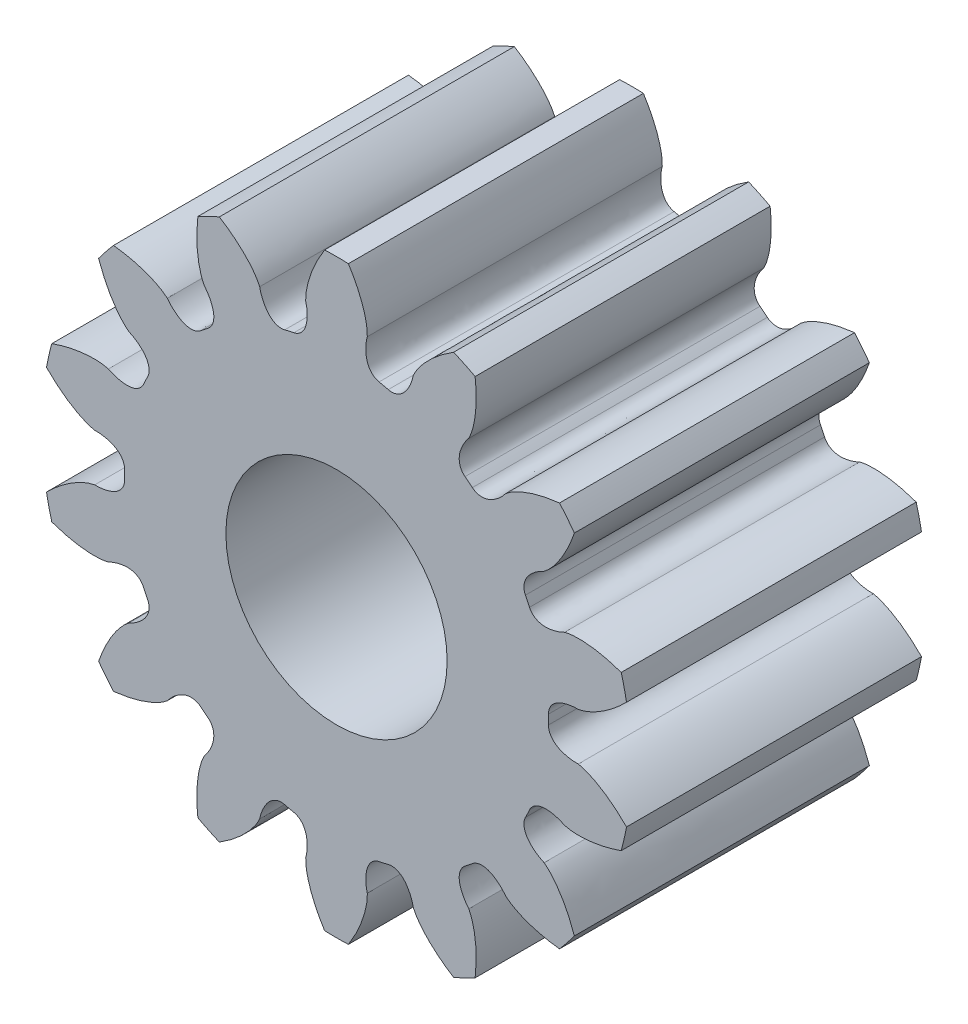
SolidWorks part; units mm, degrees
ref_plane "Спереди" through (0, 0, 0) normal (0, 0, 1) x (1, 0, 0)
ref_plane "Сверху" through (0, 0, 0) normal (0, 1, 0) x (1, 0, 0)
ref_plane "Справа" through (0, 0, 0) normal (1, 0, 0) x (0, 0, -1)
sketch "Sketch1" plane through (0, 0, 0) normal (0, 0, 1) x (1, 0, 0)
  line L0 (0, 0) -> (-5.5, 0) construction
  line L1 (0, 0) -> (5.5, 0) construction
  line L2 (0, 0) -> (0, -5.5) construction
  line L3 (0, 0) -> (0, 5.5) construction
  arc A60 (0.1615, 3.9967) -> (-0.1615, 3.9967) centre (0, 0) ccw
  arc A61 (-0.5774, 2.8164) -> (-0.7018, 2.788) centre (0, 0) ccw
  arc A62 (-1.5887, 3.671) -> (-1.8796, 3.5309) centre (0, 0) ccw
  arc A63 (-1.7422, 2.287) -> (-1.842, 2.2074) centre (0, 0) ccw
  arc A64 (-3.0241, 2.6182) -> (-3.2254, 2.3657) centre (0, 0) ccw
  arc A65 (-2.562, 1.3046) -> (-2.6173, 1.1896) centre (0, 0) ccw
  arc A66 (-3.8606, 1.0468) -> (-3.9325, 0.732) centre (0, 0) ccw
  arc A67 (-2.8743, 0.0638) -> (-2.8743, -0.0638) centre (0, 0) ccw
  arc A68 (-3.9325, -0.732) -> (-3.8606, -1.0468) centre (0, 0) ccw
  arc A69 (-2.6173, -1.1896) -> (-2.562, -1.3046) centre (0, 0) ccw
  arc A70 (-3.2254, -2.3657) -> (-3.0241, -2.6182) centre (0, 0) ccw
  arc A71 (-1.842, -2.2074) -> (-1.7422, -2.287) centre (0, 0) ccw
  arc A72 (-1.8796, -3.5309) -> (-1.5887, -3.671) centre (0, 0) ccw
  arc A73 (-0.7018, -2.788) -> (-0.5774, -2.8164) centre (0, 0) ccw
  arc A74 (-0.1615, -3.9967) -> (0.1615, -3.9967) centre (0, 0) ccw
  arc A75 (0.5774, -2.8164) -> (0.7018, -2.788) centre (0, 0) ccw
  arc A76 (1.5887, -3.671) -> (1.8796, -3.5309) centre (0, 0) ccw
  arc A77 (1.7422, -2.287) -> (1.842, -2.2074) centre (0, 0) ccw
  arc A78 (3.0241, -2.6182) -> (3.2254, -2.3657) centre (0, 0) ccw
  arc A79 (2.562, -1.3046) -> (2.6173, -1.1896) centre (0, 0) ccw
  arc A80 (3.8606, -1.0468) -> (3.9325, -0.732) centre (0, 0) ccw
  arc A81 (2.8743, -0.0638) -> (2.8743, 0.0638) centre (0, 0) ccw
  arc A82 (3.9325, 0.732) -> (3.8606, 1.0468) centre (0, 0) ccw
  arc A83 (2.6173, 1.1896) -> (2.562, 1.3046) centre (0, 0) ccw
  arc A84 (3.2254, 2.3657) -> (3.0241, 2.6182) centre (0, 0) ccw
  arc A85 (1.842, 2.2074) -> (1.7422, 2.287) centre (0, 0) ccw
  arc A86 (1.8796, 3.5309) -> (1.5887, 3.671) centre (0, 0) ccw
  arc A87 (0.7018, 2.788) -> (0.5774, 2.8164) centre (0, 0) ccw
  circle A88 centre (0, 0) radius 3.5 construction
  spline S0 degree 3 poles (0.4173, 3.2671) (0.4021, 3.2094) (0.3957, 3.1517) (0.3981, 3.0941) (0.3993, 3.0639) (0.4019, 3.033) (0.409, 3.0037) (0.4137, 2.9844) (0.4196, 2.9649) (0.4276, 2.9468) (0.4338, 2.933) (0.4408, 2.9193) (0.4492, 2.9068) (0.4561, 2.8963) (0.4638, 2.8861) (0.4724, 2.8769) (0.4799, 2.8687) (0.4882, 2.861) (0.497, 2.8541) (0.5051, 2.8477) (0.5137, 2.8419) (0.5227, 2.8368) (0.5313, 2.832) (0.5403, 2.8278) (0.5496, 2.8244) (0.5586, 2.8211) (0.5678, 2.8184) (0.5774, 2.8164) knots 0 0 0 0 1 1 1 2 2 2 3 3 3 4 4 4 5 5 5 6 6 6 7 7 7 8 8 8 9 9 9 9
  spline S1 degree 3 poles (-0.4173, 3.2671) (-0.4021, 3.2094) (-0.3957, 3.1517) (-0.3981, 3.0941) (-0.3993, 3.0639) (-0.4019, 3.033) (-0.409, 3.0037) (-0.4137, 2.9844) (-0.4196, 2.9649) (-0.4276, 2.9468) (-0.4338, 2.933) (-0.4408, 2.9193) (-0.4492, 2.9068) (-0.4561, 2.8963) (-0.4638, 2.8861) (-0.4724, 2.8769) (-0.4799, 2.8687) (-0.4882, 2.861) (-0.497, 2.8541) (-0.5051, 2.8477) (-0.5137, 2.8419) (-0.5227, 2.8368) (-0.5313, 2.832) (-0.5403, 2.8278) (-0.5496, 2.8244) (-0.5586, 2.8211) (-0.5678, 2.8184) (-0.5774, 2.8164) knots 0 0 0 0 1 1 1 2 2 2 3 3 3 4 4 4 5 5 5 6 6 6 7 7 7 8 8 8 9 9 9 9
  spline S2 degree 3 poles (0.4173, 3.2671) (0.4181, 3.2937) (0.4172, 3.3202) (0.4149, 3.3465) (0.4125, 3.3735) (0.408, 3.4004) (0.403, 3.427) (0.3978, 3.4543) (0.3913, 3.4813) (0.3842, 3.5081) (0.3769, 3.5355) (0.3685, 3.5627) (0.3596, 3.5896) (0.3504, 3.6171) (0.3403, 3.6444) (0.3296, 3.6713) (0.3186, 3.6988) (0.3069, 3.7261) (0.2946, 3.753) (0.282, 3.7805) (0.2687, 3.8077) (0.2548, 3.8346) (0.2406, 3.862) (0.2257, 3.8891) (0.2104, 3.9159) (0.1947, 3.9432) (0.1784, 3.9701) (0.1615, 3.9967) knots 0 0 0 0 1 1 1 2 2 2 3 3 3 4 4 4 5 5 5 6 6 6 7 7 7 8 8 8 9 9 9 9
  spline S3 degree 3 poles (-0.4173, 3.2671) (-0.4181, 3.2937) (-0.4172, 3.3202) (-0.4149, 3.3465) (-0.4125, 3.3735) (-0.408, 3.4004) (-0.403, 3.427) (-0.3978, 3.4543) (-0.3913, 3.4813) (-0.3842, 3.5081) (-0.3769, 3.5355) (-0.3685, 3.5627) (-0.3596, 3.5896) (-0.3504, 3.6171) (-0.3403, 3.6444) (-0.3296, 3.6713) (-0.3186, 3.6988) (-0.3069, 3.7261) (-0.2946, 3.753) (-0.282, 3.7805) (-0.2687, 3.8077) (-0.2548, 3.8346) (-0.2406, 3.862) (-0.2257, 3.8891) (-0.2104, 3.9159) (-0.1947, 3.9432) (-0.1784, 3.9701) (-0.1615, 3.9967) knots 0 0 0 0 1 1 1 2 2 2 3 3 3 4 4 4 5 5 5 6 6 6 7 7 7 8 8 8 9 9 9 9
  spline S4 degree 3 poles (-1.0415, 3.1246) (-1.0302, 3.066) (-1.011, 3.0113) (-0.9838, 2.9604) (-0.9696, 2.9338) (-0.9539, 2.907) (-0.9347, 2.8837) (-0.9221, 2.8683) (-0.9084, 2.8534) (-0.8933, 2.8405) (-0.8818, 2.8307) (-0.8695, 2.8215) (-0.8565, 2.8138) (-0.8457, 2.8073) (-0.8343, 2.8016) (-0.8226, 2.7969) (-0.8123, 2.7929) (-0.8015, 2.7895) (-0.7906, 2.7871) (-0.7805, 2.7849) (-0.7702, 2.7833) (-0.7599, 2.7827) (-0.7501, 2.7821) (-0.7401, 2.7822) (-0.7303, 2.7831) (-0.7208, 2.784) (-0.7112, 2.7857) (-0.7018, 2.788) knots 0 0 0 0 1 1 1 2 2 2 3 3 3 4 4 4 5 5 5 6 6 6 7 7 7 8 8 8 9 9 9 9
  spline S5 degree 3 poles (-1.7936, 2.7625) (-1.7548, 2.7171) (-1.724, 2.6679) (-1.7011, 2.6149) (-1.6892, 2.5872) (-1.6781, 2.5583) (-1.6718, 2.5287) (-1.6676, 2.5093) (-1.6645, 2.4893) (-1.6638, 2.4694) (-1.6634, 2.4543) (-1.6638, 2.439) (-1.6659, 2.424) (-1.6676, 2.4116) (-1.6701, 2.399) (-1.6738, 2.387) (-1.6771, 2.3764) (-1.6812, 2.3658) (-1.6861, 2.3558) (-1.6906, 2.3466) (-1.6959, 2.3375) (-1.7018, 2.3291) (-1.7075, 2.3211) (-1.7138, 2.3133) (-1.7206, 2.3063) (-1.7273, 2.2993) (-1.7345, 2.2929) (-1.7422, 2.287) knots 0 0 0 0 1 1 1 2 2 2 3 3 3 4 4 4 5 5 5 6 6 6 7 7 7 8 8 8 9 9 9 9
  spline S6 degree 3 poles (-1.0415, 3.1246) (-1.0524, 3.1489) (-1.0647, 3.1724) (-1.0782, 3.1951) (-1.092, 3.2184) (-1.1078, 3.2407) (-1.1239, 3.2625) (-1.1403, 3.2848) (-1.1579, 3.3064) (-1.176, 3.3274) (-1.1944, 3.3489) (-1.2138, 3.3698) (-1.2335, 3.3901) (-1.2537, 3.4109) (-1.2747, 3.4311) (-1.296, 3.4507) (-1.3178, 3.4708) (-1.3402, 3.4902) (-1.363, 3.5092) (-1.3862, 3.5285) (-1.4101, 3.5472) (-1.4342, 3.5654) (-1.4589, 3.5839) (-1.484, 3.6019) (-1.5095, 3.6193) (-1.5355, 3.6371) (-1.5619, 3.6544) (-1.5887, 3.671) knots 0 0 0 0 1 1 1 2 2 2 3 3 3 4 4 4 5 5 5 6 6 6 7 7 7 8 8 8 9 9 9 9
  spline S7 degree 3 poles (-1.7936, 2.7625) (-1.8057, 2.7861) (-1.8165, 2.8103) (-1.8258, 2.8351) (-1.8354, 2.8604) (-1.843, 2.8866) (-1.85, 2.9128) (-1.8572, 2.9396) (-1.8631, 2.9668) (-1.8683, 2.994) (-1.8736, 3.0219) (-1.8779, 3.05) (-1.8814, 3.0781) (-1.8851, 3.1069) (-1.8878, 3.1358) (-1.8899, 3.1647) (-1.892, 3.1943) (-1.8932, 3.2239) (-1.8938, 3.2535) (-1.8944, 3.2838) (-1.8942, 3.3141) (-1.8933, 3.3443) (-1.8924, 3.3752) (-1.8908, 3.406) (-1.8886, 3.4368) (-1.8863, 3.4682) (-1.8833, 3.4996) (-1.8796, 3.5309) knots 0 0 0 0 1 1 1 2 2 2 3 3 3 4 4 4 5 5 5 6 6 6 7 7 7 8 8 8 9 9 9 9
  spline S8 degree 3 poles (-2.2941, 2.3633) (-2.2585, 2.3154) (-2.2174, 2.2744) (-2.1708, 2.2403) (-2.1465, 2.2225) (-2.1207, 2.2053) (-2.0933, 2.1926) (-2.0753, 2.1842) (-2.0565, 2.1767) (-2.0372, 2.1716) (-2.0226, 2.1678) (-2.0076, 2.1648) (-1.9925, 2.1635) (-1.98, 2.1624) (-1.9673, 2.1621) (-1.9547, 2.163) (-1.9436, 2.1639) (-1.9324, 2.1655) (-1.9216, 2.168) (-1.9115, 2.1704) (-1.9016, 2.1735) (-1.892, 2.1774) (-1.8829, 2.1811) (-1.874, 2.1856) (-1.8656, 2.1906) (-1.8573, 2.1956) (-1.8495, 2.2012) (-1.842, 2.2074) knots 0 0 0 0 1 1 1 2 2 2 3 3 3 4 4 4 5 5 5 6 6 6 7 7 7 8 8 8 9 9 9 9
  spline S9 degree 3 poles (-2.8145, 1.7107) (-2.7599, 1.6866) (-2.7108, 1.6557) (-2.6672, 1.6179) (-2.6444, 1.5981) (-2.6219, 1.5768) (-2.6034, 1.553) (-2.5912, 1.5372) (-2.5797, 1.5206) (-2.5705, 1.5029) (-2.5635, 1.4896) (-2.5573, 1.4755) (-2.5526, 1.4612) (-2.5488, 1.4492) (-2.5457, 1.4368) (-2.5438, 1.4244) (-2.5421, 1.4134) (-2.5412, 1.4021) (-2.5413, 1.391) (-2.5413, 1.3807) (-2.5422, 1.3702) (-2.5438, 1.3601) (-2.5454, 1.3504) (-2.5478, 1.3407) (-2.5509, 1.3313) (-2.5539, 1.3222) (-2.5576, 1.3133) (-2.562, 1.3046) knots 0 0 0 0 1 1 1 2 2 2 3 3 3 4 4 4 5 5 5 6 6 6 7 7 7 8 8 8 9 9 9 9
  spline S10 degree 3 poles (-2.2941, 2.3633) (-2.3145, 2.3804) (-2.3357, 2.3963) (-2.3577, 2.4109) (-2.3803, 2.4259) (-2.4041, 2.4391) (-2.4281, 2.4518) (-2.4526, 2.4647) (-2.4778, 2.4765) (-2.5032, 2.4877) (-2.5292, 2.499) (-2.5557, 2.5095) (-2.5823, 2.5192) (-2.6095, 2.5292) (-2.6371, 2.5383) (-2.6649, 2.5467) (-2.6932, 2.5553) (-2.7218, 2.5631) (-2.7506, 2.5703) (-2.7799, 2.5776) (-2.8095, 2.5841) (-2.8391, 2.59) (-2.8694, 2.596) (-2.8999, 2.6013) (-2.9304, 2.606) (-2.9615, 2.6107) (-2.9928, 2.6148) (-3.0241, 2.6182) knots 0 0 0 0 1 1 1 2 2 2 3 3 3 4 4 4 5 5 5 6 6 6 7 7 7 8 8 8 9 9 9 9
  spline S11 degree 3 poles (-2.8145, 1.7107) (-2.8358, 1.7268) (-2.856, 1.7439) (-2.8751, 1.7621) (-2.8947, 1.7808) (-2.9129, 1.8011) (-2.9306, 1.8217) (-2.9487, 1.8427) (-2.9658, 1.8646) (-2.9823, 1.8869) (-2.9992, 1.9097) (-3.0152, 1.9332) (-3.0307, 1.957) (-3.0464, 1.9813) (-3.0614, 2.0062) (-3.0758, 2.0313) (-3.0905, 2.0571) (-3.1045, 2.0832) (-3.1179, 2.1097) (-3.1315, 2.1366) (-3.1445, 2.164) (-3.1568, 2.1916) (-3.1695, 2.2198) (-3.1814, 2.2483) (-3.1927, 2.277) (-3.2043, 2.3063) (-3.2152, 2.3359) (-3.2254, 2.3657) knots 0 0 0 0 1 1 1 2 2 2 3 3 3 4 4 4 5 5 5 6 6 6 7 7 7 8 8 8 9 9 9 9
  spline S12 degree 3 poles (-3.0923, 1.1339) (-3.0394, 1.1062) (-2.9846, 1.0871) (-2.9279, 1.0766) (-2.8982, 1.0711) (-2.8675, 1.0667) (-2.8373, 1.0672) (-2.8175, 1.0674) (-2.7972, 1.0688) (-2.7777, 1.0726) (-2.7629, 1.0755) (-2.748, 1.0794) (-2.7339, 1.0847) (-2.7222, 1.0891) (-2.7105, 1.0944) (-2.6996, 1.1007) (-2.69, 1.1063) (-2.6806, 1.1126) (-2.672, 1.1196) (-2.6639, 1.1261) (-2.6563, 1.1332) (-2.6494, 1.1409) (-2.6428, 1.1482) (-2.6367, 1.156) (-2.6313, 1.1643) (-2.626, 1.1723) (-2.6214, 1.1808) (-2.6173, 1.1896) knots 0 0 0 0 1 1 1 2 2 2 3 3 3 4 4 4 5 5 5 6 6 6 7 7 7 8 8 8 9 9 9 9
  spline S13 degree 3 poles (-3.2781, 0.3201) (-3.2184, 0.3221) (-3.1607, 0.3155) (-3.1051, 0.3004) (-3.076, 0.2925) (-3.0464, 0.2831) (-3.0194, 0.2696) (-3.0016, 0.2607) (-2.984, 0.2507) (-2.968, 0.2388) (-2.9559, 0.2298) (-2.9442, 0.2198) (-2.9338, 0.2089) (-2.9251, 0.1998) (-2.917, 0.19) (-2.9099, 0.1796) (-2.9036, 0.1704) (-2.8979, 0.1607) (-2.8931, 0.1506) (-2.8887, 0.1413) (-2.8849, 0.1315) (-2.882, 0.1216) (-2.8793, 0.1122) (-2.8772, 0.1025) (-2.8759, 0.0927) (-2.8746, 0.0832) (-2.8741, 0.0735) (-2.8743, 0.0638) knots 0 0 0 0 1 1 1 2 2 2 3 3 3 4 4 4 5 5 5 6 6 6 7 7 7 8 8 8 9 9 9 9
  spline S14 degree 3 poles (-3.0923, 1.1339) (-3.1181, 1.1405) (-3.1441, 1.1456) (-3.1703, 1.1492) (-3.1971, 1.1528) (-3.2243, 1.1544) (-3.2514, 1.1554) (-3.2791, 1.1565) (-3.307, 1.1562) (-3.3347, 1.1552) (-3.363, 1.1542) (-3.3914, 1.1521) (-3.4196, 1.1493) (-3.4485, 1.1465) (-3.4773, 1.1427) (-3.5059, 1.1383) (-3.5352, 1.1337) (-3.5644, 1.1283) (-3.5934, 1.1223) (-3.623, 1.1162) (-3.6525, 1.1092) (-3.6817, 1.1017) (-3.7116, 1.094) (-3.7414, 1.0855) (-3.7709, 1.0764) (-3.801, 1.0672) (-3.8309, 1.0573) (-3.8606, 1.0468) knots 0 0 0 0 1 1 1 2 2 2 3 3 3 4 4 4 5 5 5 6 6 6 7 7 7 8 8 8 9 9 9 9
  spline S15 degree 3 poles (-3.2781, 0.3201) (-3.3042, 0.3254) (-3.3298, 0.332) (-3.3549, 0.3402) (-3.3807, 0.3485) (-3.4059, 0.3589) (-3.4308, 0.3697) (-3.4562, 0.3808) (-3.4811, 0.3932) (-3.5057, 0.4061) (-3.5308, 0.4193) (-3.5554, 0.4335) (-3.5796, 0.4482) (-3.6044, 0.4633) (-3.6287, 0.4792) (-3.6526, 0.4956) (-3.677, 0.5124) (-3.7009, 0.5299) (-3.7245, 0.5479) (-3.7485, 0.5663) (-3.772, 0.5854) (-3.7951, 0.6049) (-3.8187, 0.6248) (-3.8418, 0.6453) (-3.8645, 0.6663) (-3.8876, 0.6877) (-3.9103, 0.7096) (-3.9325, 0.732) knots 0 0 0 0 1 1 1 2 2 2 3 3 3 4 4 4 5 5 5 6 6 6 7 7 7 8 8 8 9 9 9 9
  spline S16 degree 3 poles (-3.2781, -0.3201) (-3.2184, -0.3221) (-3.1607, -0.3155) (-3.1051, -0.3004) (-3.076, -0.2925) (-3.0464, -0.2831) (-3.0194, -0.2696) (-3.0016, -0.2607) (-2.984, -0.2507) (-2.968, -0.2388) (-2.9559, -0.2298) (-2.9442, -0.2198) (-2.9338, -0.2089) (-2.9251, -0.1998) (-2.917, -0.19) (-2.9099, -0.1796) (-2.9036, -0.1704) (-2.8979, -0.1607) (-2.8931, -0.1506) (-2.8887, -0.1413) (-2.8849, -0.1315) (-2.882, -0.1216) (-2.8793, -0.1122) (-2.8772, -0.1025) (-2.8759, -0.0927) (-2.8746, -0.0832) (-2.8741, -0.0735) (-2.8743, -0.0638) knots 0 0 0 0 1 1 1 2 2 2 3 3 3 4 4 4 5 5 5 6 6 6 7 7 7 8 8 8 9 9 9 9
  spline S17 degree 3 poles (-3.0923, -1.1339) (-3.0394, -1.1062) (-2.9846, -1.0871) (-2.9279, -1.0766) (-2.8982, -1.0711) (-2.8675, -1.0667) (-2.8373, -1.0672) (-2.8175, -1.0674) (-2.7972, -1.0688) (-2.7777, -1.0726) (-2.7629, -1.0755) (-2.748, -1.0794) (-2.7339, -1.0847) (-2.7222, -1.0891) (-2.7105, -1.0944) (-2.6996, -1.1007) (-2.69, -1.1063) (-2.6806, -1.1126) (-2.672, -1.1196) (-2.6639, -1.1261) (-2.6563, -1.1332) (-2.6494, -1.1409) (-2.6428, -1.1482) (-2.6367, -1.156) (-2.6313, -1.1643) (-2.626, -1.1723) (-2.6214, -1.1808) (-2.6173, -1.1896) knots 0 0 0 0 1 1 1 2 2 2 3 3 3 4 4 4 5 5 5 6 6 6 7 7 7 8 8 8 9 9 9 9
  spline S18 degree 3 poles (-3.2781, -0.3201) (-3.3042, -0.3254) (-3.3298, -0.332) (-3.3549, -0.3402) (-3.3807, -0.3485) (-3.4059, -0.3589) (-3.4308, -0.3697) (-3.4562, -0.3808) (-3.4811, -0.3932) (-3.5057, -0.4061) (-3.5308, -0.4193) (-3.5554, -0.4335) (-3.5796, -0.4482) (-3.6044, -0.4633) (-3.6287, -0.4792) (-3.6526, -0.4956) (-3.677, -0.5124) (-3.7009, -0.5299) (-3.7245, -0.5479) (-3.7485, -0.5663) (-3.772, -0.5854) (-3.7951, -0.6049) (-3.8187, -0.6248) (-3.8418, -0.6453) (-3.8645, -0.6663) (-3.8876, -0.6877) (-3.9103, -0.7096) (-3.9325, -0.732) knots 0 0 0 0 1 1 1 2 2 2 3 3 3 4 4 4 5 5 5 6 6 6 7 7 7 8 8 8 9 9 9 9
  spline S19 degree 3 poles (-3.0923, -1.1339) (-3.1181, -1.1405) (-3.1441, -1.1456) (-3.1703, -1.1492) (-3.1971, -1.1528) (-3.2243, -1.1544) (-3.2514, -1.1554) (-3.2791, -1.1565) (-3.307, -1.1562) (-3.3347, -1.1552) (-3.363, -1.1542) (-3.3914, -1.1521) (-3.4196, -1.1493) (-3.4485, -1.1465) (-3.4773, -1.1427) (-3.5059, -1.1383) (-3.5352, -1.1337) (-3.5644, -1.1283) (-3.5934, -1.1223) (-3.623, -1.1162) (-3.6525, -1.1092) (-3.6817, -1.1017) (-3.7116, -1.094) (-3.7414, -1.0855) (-3.7709, -1.0764) (-3.801, -1.0672) (-3.8309, -1.0573) (-3.8606, -1.0468) knots 0 0 0 0 1 1 1 2 2 2 3 3 3 4 4 4 5 5 5 6 6 6 7 7 7 8 8 8 9 9 9 9
  spline S20 degree 3 poles (-2.8145, -1.7107) (-2.7599, -1.6866) (-2.7108, -1.6557) (-2.6672, -1.6179) (-2.6444, -1.5981) (-2.6219, -1.5768) (-2.6034, -1.553) (-2.5912, -1.5372) (-2.5797, -1.5206) (-2.5705, -1.5029) (-2.5635, -1.4896) (-2.5573, -1.4755) (-2.5526, -1.4612) (-2.5488, -1.4492) (-2.5457, -1.4368) (-2.5438, -1.4244) (-2.5421, -1.4134) (-2.5412, -1.4021) (-2.5413, -1.391) (-2.5413, -1.3807) (-2.5422, -1.3702) (-2.5438, -1.3601) (-2.5454, -1.3504) (-2.5478, -1.3407) (-2.5509, -1.3313) (-2.5539, -1.3222) (-2.5576, -1.3133) (-2.562, -1.3046) knots 0 0 0 0 1 1 1 2 2 2 3 3 3 4 4 4 5 5 5 6 6 6 7 7 7 8 8 8 9 9 9 9
  spline S21 degree 3 poles (-2.2941, -2.3633) (-2.2585, -2.3154) (-2.2174, -2.2744) (-2.1708, -2.2403) (-2.1465, -2.2225) (-2.1207, -2.2053) (-2.0933, -2.1926) (-2.0753, -2.1842) (-2.0565, -2.1767) (-2.0372, -2.1716) (-2.0226, -2.1678) (-2.0076, -2.1648) (-1.9925, -2.1635) (-1.98, -2.1624) (-1.9673, -2.1621) (-1.9547, -2.163) (-1.9436, -2.1639) (-1.9324, -2.1655) (-1.9216, -2.168) (-1.9115, -2.1704) (-1.9016, -2.1735) (-1.892, -2.1774) (-1.8829, -2.1811) (-1.874, -2.1856) (-1.8656, -2.1906) (-1.8573, -2.1956) (-1.8495, -2.2012) (-1.842, -2.2074) knots 0 0 0 0 1 1 1 2 2 2 3 3 3 4 4 4 5 5 5 6 6 6 7 7 7 8 8 8 9 9 9 9
  spline S22 degree 3 poles (-2.8145, -1.7107) (-2.8358, -1.7268) (-2.856, -1.7439) (-2.8751, -1.7621) (-2.8947, -1.7808) (-2.9129, -1.8011) (-2.9306, -1.8217) (-2.9487, -1.8427) (-2.9658, -1.8646) (-2.9823, -1.8869) (-2.9992, -1.9097) (-3.0152, -1.9332) (-3.0307, -1.957) (-3.0464, -1.9813) (-3.0614, -2.0062) (-3.0758, -2.0313) (-3.0905, -2.0571) (-3.1045, -2.0832) (-3.1179, -2.1097) (-3.1315, -2.1366) (-3.1445, -2.164) (-3.1568, -2.1916) (-3.1695, -2.2198) (-3.1814, -2.2483) (-3.1927, -2.277) (-3.2043, -2.3063) (-3.2152, -2.3359) (-3.2254, -2.3657) knots 0 0 0 0 1 1 1 2 2 2 3 3 3 4 4 4 5 5 5 6 6 6 7 7 7 8 8 8 9 9 9 9
  spline S23 degree 3 poles (-2.2941, -2.3633) (-2.3145, -2.3804) (-2.3357, -2.3963) (-2.3577, -2.4109) (-2.3803, -2.4259) (-2.4041, -2.4391) (-2.4281, -2.4518) (-2.4526, -2.4647) (-2.4778, -2.4765) (-2.5032, -2.4877) (-2.5292, -2.499) (-2.5557, -2.5095) (-2.5823, -2.5192) (-2.6095, -2.5292) (-2.6371, -2.5383) (-2.6649, -2.5467) (-2.6932, -2.5553) (-2.7218, -2.5631) (-2.7506, -2.5703) (-2.7799, -2.5776) (-2.8095, -2.5841) (-2.8391, -2.59) (-2.8694, -2.596) (-2.8999, -2.6013) (-2.9304, -2.606) (-2.9615, -2.6107) (-2.9928, -2.6148) (-3.0241, -2.6182) knots 0 0 0 0 1 1 1 2 2 2 3 3 3 4 4 4 5 5 5 6 6 6 7 7 7 8 8 8 9 9 9 9
  spline S24 degree 3 poles (-1.7936, -2.7625) (-1.7548, -2.7171) (-1.724, -2.6679) (-1.7011, -2.6149) (-1.6892, -2.5872) (-1.6781, -2.5583) (-1.6718, -2.5287) (-1.6676, -2.5093) (-1.6645, -2.4893) (-1.6638, -2.4694) (-1.6634, -2.4543) (-1.6638, -2.439) (-1.6659, -2.424) (-1.6676, -2.4116) (-1.6701, -2.399) (-1.6738, -2.387) (-1.6771, -2.3764) (-1.6812, -2.3658) (-1.6861, -2.3558) (-1.6906, -2.3466) (-1.6959, -2.3375) (-1.7018, -2.3291) (-1.7075, -2.3211) (-1.7138, -2.3133) (-1.7206, -2.3063) (-1.7273, -2.2993) (-1.7345, -2.2929) (-1.7422, -2.287) knots 0 0 0 0 1 1 1 2 2 2 3 3 3 4 4 4 5 5 5 6 6 6 7 7 7 8 8 8 9 9 9 9
  spline S25 degree 3 poles (-1.0415, -3.1246) (-1.0302, -3.066) (-1.011, -3.0113) (-0.9838, -2.9604) (-0.9696, -2.9338) (-0.9539, -2.907) (-0.9347, -2.8837) (-0.9221, -2.8683) (-0.9084, -2.8534) (-0.8933, -2.8405) (-0.8818, -2.8307) (-0.8695, -2.8215) (-0.8565, -2.8138) (-0.8457, -2.8073) (-0.8343, -2.8016) (-0.8226, -2.7969) (-0.8123, -2.7929) (-0.8015, -2.7895) (-0.7906, -2.7871) (-0.7805, -2.7849) (-0.7702, -2.7833) (-0.7599, -2.7827) (-0.7501, -2.7821) (-0.7401, -2.7822) (-0.7303, -2.7831) (-0.7208, -2.784) (-0.7112, -2.7857) (-0.7018, -2.788) knots 0 0 0 0 1 1 1 2 2 2 3 3 3 4 4 4 5 5 5 6 6 6 7 7 7 8 8 8 9 9 9 9
  spline S26 degree 3 poles (-1.7936, -2.7625) (-1.8057, -2.7861) (-1.8165, -2.8103) (-1.8258, -2.8351) (-1.8354, -2.8604) (-1.843, -2.8866) (-1.85, -2.9128) (-1.8572, -2.9396) (-1.8631, -2.9668) (-1.8683, -2.994) (-1.8736, -3.0219) (-1.8779, -3.05) (-1.8814, -3.0781) (-1.8851, -3.1069) (-1.8878, -3.1358) (-1.8899, -3.1647) (-1.892, -3.1943) (-1.8932, -3.2239) (-1.8938, -3.2535) (-1.8944, -3.2838) (-1.8942, -3.3141) (-1.8933, -3.3443) (-1.8924, -3.3752) (-1.8908, -3.406) (-1.8886, -3.4368) (-1.8863, -3.4682) (-1.8833, -3.4996) (-1.8796, -3.5309) knots 0 0 0 0 1 1 1 2 2 2 3 3 3 4 4 4 5 5 5 6 6 6 7 7 7 8 8 8 9 9 9 9
  spline S27 degree 3 poles (-1.0415, -3.1246) (-1.0524, -3.1489) (-1.0647, -3.1724) (-1.0782, -3.1951) (-1.092, -3.2184) (-1.1078, -3.2407) (-1.1239, -3.2625) (-1.1403, -3.2848) (-1.1579, -3.3064) (-1.176, -3.3274) (-1.1944, -3.3489) (-1.2138, -3.3698) (-1.2335, -3.3901) (-1.2537, -3.4109) (-1.2747, -3.4311) (-1.296, -3.4507) (-1.3178, -3.4708) (-1.3402, -3.4902) (-1.363, -3.5092) (-1.3862, -3.5285) (-1.4101, -3.5472) (-1.4342, -3.5654) (-1.4589, -3.5839) (-1.484, -3.6019) (-1.5095, -3.6193) (-1.5355, -3.6371) (-1.5619, -3.6544) (-1.5887, -3.671) knots 0 0 0 0 1 1 1 2 2 2 3 3 3 4 4 4 5 5 5 6 6 6 7 7 7 8 8 8 9 9 9 9
  spline S28 degree 3 poles (-0.4173, -3.2671) (-0.4021, -3.2094) (-0.3957, -3.1517) (-0.3981, -3.0941) (-0.3993, -3.0639) (-0.4019, -3.033) (-0.409, -3.0037) (-0.4137, -2.9844) (-0.4196, -2.9649) (-0.4276, -2.9468) (-0.4338, -2.933) (-0.4408, -2.9193) (-0.4492, -2.9068) (-0.4561, -2.8963) (-0.4638, -2.8861) (-0.4724, -2.8769) (-0.4799, -2.8687) (-0.4882, -2.861) (-0.497, -2.8541) (-0.5051, -2.8477) (-0.5137, -2.8419) (-0.5227, -2.8368) (-0.5313, -2.832) (-0.5403, -2.8278) (-0.5496, -2.8244) (-0.5586, -2.8211) (-0.5678, -2.8184) (-0.5774, -2.8164) knots 0 0 0 0 1 1 1 2 2 2 3 3 3 4 4 4 5 5 5 6 6 6 7 7 7 8 8 8 9 9 9 9
  spline S29 degree 3 poles (0.4173, -3.2671) (0.4021, -3.2094) (0.3957, -3.1517) (0.3981, -3.0941) (0.3993, -3.0639) (0.4019, -3.033) (0.409, -3.0037) (0.4137, -2.9844) (0.4196, -2.9649) (0.4276, -2.9468) (0.4338, -2.933) (0.4408, -2.9193) (0.4492, -2.9068) (0.4561, -2.8963) (0.4638, -2.8861) (0.4724, -2.8769) (0.4799, -2.8687) (0.4882, -2.861) (0.497, -2.8541) (0.5051, -2.8477) (0.5137, -2.8419) (0.5227, -2.8368) (0.5313, -2.832) (0.5403, -2.8278) (0.5496, -2.8244) (0.5586, -2.8211) (0.5678, -2.8184) (0.5774, -2.8164) knots 0 0 0 0 1 1 1 2 2 2 3 3 3 4 4 4 5 5 5 6 6 6 7 7 7 8 8 8 9 9 9 9
  spline S30 degree 3 poles (-0.4173, -3.2671) (-0.4181, -3.2937) (-0.4172, -3.3202) (-0.4149, -3.3465) (-0.4125, -3.3735) (-0.408, -3.4004) (-0.403, -3.427) (-0.3978, -3.4543) (-0.3913, -3.4813) (-0.3842, -3.5081) (-0.3769, -3.5355) (-0.3685, -3.5627) (-0.3596, -3.5896) (-0.3504, -3.6171) (-0.3403, -3.6444) (-0.3296, -3.6713) (-0.3186, -3.6988) (-0.3069, -3.7261) (-0.2946, -3.753) (-0.282, -3.7805) (-0.2687, -3.8077) (-0.2548, -3.8346) (-0.2406, -3.862) (-0.2257, -3.8891) (-0.2104, -3.9159) (-0.1947, -3.9432) (-0.1784, -3.9701) (-0.1615, -3.9967) knots 0 0 0 0 1 1 1 2 2 2 3 3 3 4 4 4 5 5 5 6 6 6 7 7 7 8 8 8 9 9 9 9
  spline S31 degree 3 poles (0.4173, -3.2671) (0.4181, -3.2937) (0.4172, -3.3202) (0.4149, -3.3465) (0.4125, -3.3735) (0.408, -3.4004) (0.403, -3.427) (0.3978, -3.4543) (0.3913, -3.4813) (0.3842, -3.5081) (0.3769, -3.5355) (0.3685, -3.5627) (0.3596, -3.5896) (0.3504, -3.6171) (0.3403, -3.6444) (0.3296, -3.6713) (0.3186, -3.6988) (0.3069, -3.7261) (0.2946, -3.753) (0.282, -3.7805) (0.2687, -3.8077) (0.2548, -3.8346) (0.2406, -3.862) (0.2257, -3.8891) (0.2104, -3.9159) (0.1947, -3.9432) (0.1784, -3.9701) (0.1615, -3.9967) knots 0 0 0 0 1 1 1 2 2 2 3 3 3 4 4 4 5 5 5 6 6 6 7 7 7 8 8 8 9 9 9 9
  spline S32 degree 3 poles (1.0415, -3.1246) (1.0302, -3.066) (1.011, -3.0113) (0.9838, -2.9604) (0.9696, -2.9338) (0.9539, -2.907) (0.9347, -2.8837) (0.9221, -2.8683) (0.9084, -2.8534) (0.8933, -2.8405) (0.8818, -2.8307) (0.8695, -2.8215) (0.8565, -2.8138) (0.8457, -2.8073) (0.8343, -2.8016) (0.8226, -2.7969) (0.8123, -2.7929) (0.8015, -2.7895) (0.7906, -2.7871) (0.7805, -2.7849) (0.7702, -2.7833) (0.7599, -2.7827) (0.7501, -2.7821) (0.7401, -2.7822) (0.7303, -2.7831) (0.7208, -2.784) (0.7112, -2.7857) (0.7018, -2.788) knots 0 0 0 0 1 1 1 2 2 2 3 3 3 4 4 4 5 5 5 6 6 6 7 7 7 8 8 8 9 9 9 9
  spline S33 degree 3 poles (1.7936, -2.7625) (1.7548, -2.7171) (1.724, -2.6679) (1.7011, -2.6149) (1.6892, -2.5872) (1.6781, -2.5583) (1.6718, -2.5287) (1.6676, -2.5093) (1.6645, -2.4893) (1.6638, -2.4694) (1.6634, -2.4543) (1.6638, -2.439) (1.6659, -2.424) (1.6676, -2.4116) (1.6701, -2.399) (1.6738, -2.387) (1.6771, -2.3764) (1.6812, -2.3658) (1.6861, -2.3558) (1.6906, -2.3466) (1.6959, -2.3375) (1.7018, -2.3291) (1.7075, -2.3211) (1.7138, -2.3133) (1.7206, -2.3063) (1.7273, -2.2993) (1.7345, -2.2929) (1.7422, -2.287) knots 0 0 0 0 1 1 1 2 2 2 3 3 3 4 4 4 5 5 5 6 6 6 7 7 7 8 8 8 9 9 9 9
  spline S34 degree 3 poles (1.0415, -3.1246) (1.0524, -3.1489) (1.0647, -3.1724) (1.0782, -3.1951) (1.092, -3.2184) (1.1078, -3.2407) (1.1239, -3.2625) (1.1403, -3.2848) (1.1579, -3.3064) (1.176, -3.3274) (1.1944, -3.3489) (1.2138, -3.3698) (1.2335, -3.3901) (1.2537, -3.4109) (1.2747, -3.4311) (1.296, -3.4507) (1.3178, -3.4708) (1.3402, -3.4902) (1.363, -3.5092) (1.3862, -3.5285) (1.4101, -3.5472) (1.4342, -3.5654) (1.4589, -3.5839) (1.484, -3.6019) (1.5095, -3.6193) (1.5355, -3.6371) (1.5619, -3.6544) (1.5887, -3.671) knots 0 0 0 0 1 1 1 2 2 2 3 3 3 4 4 4 5 5 5 6 6 6 7 7 7 8 8 8 9 9 9 9
  spline S35 degree 3 poles (1.7936, -2.7625) (1.8057, -2.7861) (1.8165, -2.8103) (1.8258, -2.8351) (1.8354, -2.8604) (1.843, -2.8866) (1.85, -2.9128) (1.8572, -2.9396) (1.8631, -2.9668) (1.8683, -2.994) (1.8736, -3.0219) (1.8779, -3.05) (1.8814, -3.0781) (1.8851, -3.1069) (1.8878, -3.1358) (1.8899, -3.1647) (1.892, -3.1943) (1.8932, -3.2239) (1.8938, -3.2535) (1.8944, -3.2838) (1.8942, -3.3141) (1.8933, -3.3443) (1.8924, -3.3752) (1.8908, -3.406) (1.8886, -3.4368) (1.8863, -3.4682) (1.8833, -3.4996) (1.8796, -3.5309) knots 0 0 0 0 1 1 1 2 2 2 3 3 3 4 4 4 5 5 5 6 6 6 7 7 7 8 8 8 9 9 9 9
  spline S36 degree 3 poles (2.2941, -2.3633) (2.2585, -2.3154) (2.2174, -2.2744) (2.1708, -2.2403) (2.1465, -2.2225) (2.1207, -2.2053) (2.0933, -2.1926) (2.0753, -2.1842) (2.0565, -2.1767) (2.0372, -2.1716) (2.0226, -2.1678) (2.0076, -2.1648) (1.9925, -2.1635) (1.98, -2.1624) (1.9673, -2.1621) (1.9547, -2.163) (1.9436, -2.1639) (1.9324, -2.1655) (1.9216, -2.168) (1.9115, -2.1704) (1.9016, -2.1735) (1.892, -2.1774) (1.8829, -2.1811) (1.874, -2.1856) (1.8656, -2.1906) (1.8573, -2.1956) (1.8495, -2.2012) (1.842, -2.2074) knots 0 0 0 0 1 1 1 2 2 2 3 3 3 4 4 4 5 5 5 6 6 6 7 7 7 8 8 8 9 9 9 9
  spline S37 degree 3 poles (2.8145, -1.7107) (2.7599, -1.6866) (2.7108, -1.6557) (2.6672, -1.6179) (2.6444, -1.5981) (2.6219, -1.5768) (2.6034, -1.553) (2.5912, -1.5372) (2.5797, -1.5206) (2.5705, -1.5029) (2.5635, -1.4896) (2.5573, -1.4755) (2.5526, -1.4612) (2.5488, -1.4492) (2.5457, -1.4368) (2.5438, -1.4244) (2.5421, -1.4134) (2.5412, -1.4021) (2.5413, -1.391) (2.5413, -1.3807) (2.5422, -1.3702) (2.5438, -1.3601) (2.5454, -1.3504) (2.5478, -1.3407) (2.5509, -1.3313) (2.5539, -1.3222) (2.5576, -1.3133) (2.562, -1.3046) knots 0 0 0 0 1 1 1 2 2 2 3 3 3 4 4 4 5 5 5 6 6 6 7 7 7 8 8 8 9 9 9 9
  spline S38 degree 3 poles (2.2941, -2.3633) (2.3145, -2.3804) (2.3357, -2.3963) (2.3577, -2.4109) (2.3803, -2.4259) (2.4041, -2.4391) (2.4281, -2.4518) (2.4526, -2.4647) (2.4778, -2.4765) (2.5032, -2.4877) (2.5292, -2.499) (2.5557, -2.5095) (2.5823, -2.5192) (2.6095, -2.5292) (2.6371, -2.5383) (2.6649, -2.5467) (2.6932, -2.5553) (2.7218, -2.5631) (2.7506, -2.5703) (2.7799, -2.5776) (2.8095, -2.5841) (2.8391, -2.59) (2.8694, -2.596) (2.8999, -2.6013) (2.9304, -2.606) (2.9615, -2.6107) (2.9928, -2.6148) (3.0241, -2.6182) knots 0 0 0 0 1 1 1 2 2 2 3 3 3 4 4 4 5 5 5 6 6 6 7 7 7 8 8 8 9 9 9 9
  spline S39 degree 3 poles (2.8145, -1.7107) (2.8358, -1.7268) (2.856, -1.7439) (2.8751, -1.7621) (2.8947, -1.7808) (2.9129, -1.8011) (2.9306, -1.8217) (2.9487, -1.8427) (2.9658, -1.8646) (2.9823, -1.8869) (2.9992, -1.9097) (3.0152, -1.9332) (3.0307, -1.957) (3.0464, -1.9813) (3.0614, -2.0062) (3.0758, -2.0313) (3.0905, -2.0571) (3.1045, -2.0832) (3.1179, -2.1097) (3.1315, -2.1366) (3.1445, -2.164) (3.1568, -2.1916) (3.1695, -2.2198) (3.1814, -2.2483) (3.1927, -2.277) (3.2043, -2.3063) (3.2152, -2.3359) (3.2254, -2.3657) knots 0 0 0 0 1 1 1 2 2 2 3 3 3 4 4 4 5 5 5 6 6 6 7 7 7 8 8 8 9 9 9 9
  spline S40 degree 3 poles (3.0923, -1.1339) (3.0394, -1.1062) (2.9846, -1.0871) (2.9279, -1.0766) (2.8982, -1.0711) (2.8675, -1.0667) (2.8373, -1.0672) (2.8175, -1.0674) (2.7972, -1.0688) (2.7777, -1.0726) (2.7629, -1.0755) (2.748, -1.0794) (2.7339, -1.0847) (2.7222, -1.0891) (2.7105, -1.0944) (2.6996, -1.1007) (2.69, -1.1063) (2.6806, -1.1126) (2.672, -1.1196) (2.6639, -1.1261) (2.6563, -1.1332) (2.6494, -1.1409) (2.6428, -1.1482) (2.6367, -1.156) (2.6313, -1.1643) (2.626, -1.1723) (2.6214, -1.1808) (2.6173, -1.1896) knots 0 0 0 0 1 1 1 2 2 2 3 3 3 4 4 4 5 5 5 6 6 6 7 7 7 8 8 8 9 9 9 9
  spline S41 degree 3 poles (3.2781, -0.3201) (3.2184, -0.3221) (3.1607, -0.3155) (3.1051, -0.3004) (3.076, -0.2925) (3.0464, -0.2831) (3.0194, -0.2696) (3.0016, -0.2607) (2.984, -0.2507) (2.968, -0.2388) (2.9559, -0.2298) (2.9442, -0.2198) (2.9338, -0.2089) (2.9251, -0.1998) (2.917, -0.19) (2.9099, -0.1796) (2.9036, -0.1704) (2.8979, -0.1607) (2.8931, -0.1506) (2.8887, -0.1413) (2.8849, -0.1315) (2.882, -0.1216) (2.8793, -0.1122) (2.8772, -0.1025) (2.8759, -0.0927) (2.8746, -0.0832) (2.8741, -0.0735) (2.8743, -0.0638) knots 0 0 0 0 1 1 1 2 2 2 3 3 3 4 4 4 5 5 5 6 6 6 7 7 7 8 8 8 9 9 9 9
  spline S42 degree 3 poles (3.0923, -1.1339) (3.1181, -1.1405) (3.1441, -1.1456) (3.1703, -1.1492) (3.1971, -1.1528) (3.2243, -1.1544) (3.2514, -1.1554) (3.2791, -1.1565) (3.307, -1.1562) (3.3347, -1.1552) (3.363, -1.1542) (3.3914, -1.1521) (3.4196, -1.1493) (3.4485, -1.1465) (3.4773, -1.1427) (3.5059, -1.1383) (3.5352, -1.1337) (3.5644, -1.1283) (3.5934, -1.1223) (3.623, -1.1162) (3.6525, -1.1092) (3.6817, -1.1017) (3.7116, -1.094) (3.7414, -1.0855) (3.7709, -1.0764) (3.801, -1.0672) (3.8309, -1.0573) (3.8606, -1.0468) knots 0 0 0 0 1 1 1 2 2 2 3 3 3 4 4 4 5 5 5 6 6 6 7 7 7 8 8 8 9 9 9 9
  spline S43 degree 3 poles (3.2781, -0.3201) (3.3042, -0.3254) (3.3298, -0.332) (3.3549, -0.3402) (3.3807, -0.3485) (3.4059, -0.3589) (3.4308, -0.3697) (3.4562, -0.3808) (3.4811, -0.3932) (3.5057, -0.4061) (3.5308, -0.4193) (3.5554, -0.4335) (3.5796, -0.4482) (3.6044, -0.4633) (3.6287, -0.4792) (3.6526, -0.4956) (3.677, -0.5124) (3.7009, -0.5299) (3.7245, -0.5479) (3.7485, -0.5663) (3.772, -0.5854) (3.7951, -0.6049) (3.8187, -0.6248) (3.8418, -0.6453) (3.8645, -0.6663) (3.8876, -0.6877) (3.9103, -0.7096) (3.9325, -0.732) knots 0 0 0 0 1 1 1 2 2 2 3 3 3 4 4 4 5 5 5 6 6 6 7 7 7 8 8 8 9 9 9 9
  spline S44 degree 3 poles (3.2781, 0.3201) (3.2184, 0.3221) (3.1607, 0.3155) (3.1051, 0.3004) (3.076, 0.2925) (3.0464, 0.2831) (3.0194, 0.2696) (3.0016, 0.2607) (2.984, 0.2507) (2.968, 0.2388) (2.9559, 0.2298) (2.9442, 0.2198) (2.9338, 0.2089) (2.9251, 0.1998) (2.917, 0.19) (2.9099, 0.1796) (2.9036, 0.1704) (2.8979, 0.1607) (2.8931, 0.1506) (2.8887, 0.1413) (2.8849, 0.1315) (2.882, 0.1216) (2.8793, 0.1122) (2.8772, 0.1025) (2.8759, 0.0927) (2.8746, 0.0832) (2.8741, 0.0735) (2.8743, 0.0638) knots 0 0 0 0 1 1 1 2 2 2 3 3 3 4 4 4 5 5 5 6 6 6 7 7 7 8 8 8 9 9 9 9
  spline S45 degree 3 poles (3.0923, 1.1339) (3.0394, 1.1062) (2.9846, 1.0871) (2.9279, 1.0766) (2.8982, 1.0711) (2.8675, 1.0667) (2.8373, 1.0672) (2.8175, 1.0674) (2.7972, 1.0688) (2.7777, 1.0726) (2.7629, 1.0755) (2.748, 1.0794) (2.7339, 1.0847) (2.7222, 1.0891) (2.7105, 1.0944) (2.6996, 1.1007) (2.69, 1.1063) (2.6806, 1.1126) (2.672, 1.1196) (2.6639, 1.1261) (2.6563, 1.1332) (2.6494, 1.1409) (2.6428, 1.1482) (2.6367, 1.156) (2.6313, 1.1643) (2.626, 1.1723) (2.6214, 1.1808) (2.6173, 1.1896) knots 0 0 0 0 1 1 1 2 2 2 3 3 3 4 4 4 5 5 5 6 6 6 7 7 7 8 8 8 9 9 9 9
  spline S46 degree 3 poles (3.2781, 0.3201) (3.3042, 0.3254) (3.3298, 0.332) (3.3549, 0.3402) (3.3807, 0.3485) (3.4059, 0.3589) (3.4308, 0.3697) (3.4562, 0.3808) (3.4811, 0.3932) (3.5057, 0.4061) (3.5308, 0.4193) (3.5554, 0.4335) (3.5796, 0.4482) (3.6044, 0.4633) (3.6287, 0.4792) (3.6526, 0.4956) (3.677, 0.5124) (3.7009, 0.5299) (3.7245, 0.5479) (3.7485, 0.5663) (3.772, 0.5854) (3.7951, 0.6049) (3.8187, 0.6248) (3.8418, 0.6453) (3.8645, 0.6663) (3.8876, 0.6877) (3.9103, 0.7096) (3.9325, 0.732) knots 0 0 0 0 1 1 1 2 2 2 3 3 3 4 4 4 5 5 5 6 6 6 7 7 7 8 8 8 9 9 9 9
  spline S47 degree 3 poles (3.0923, 1.1339) (3.1181, 1.1405) (3.1441, 1.1456) (3.1703, 1.1492) (3.1971, 1.1528) (3.2243, 1.1544) (3.2514, 1.1554) (3.2791, 1.1565) (3.307, 1.1562) (3.3347, 1.1552) (3.363, 1.1542) (3.3914, 1.1521) (3.4196, 1.1493) (3.4485, 1.1465) (3.4773, 1.1427) (3.5059, 1.1383) (3.5352, 1.1337) (3.5644, 1.1283) (3.5934, 1.1223) (3.623, 1.1162) (3.6525, 1.1092) (3.6817, 1.1017) (3.7116, 1.094) (3.7414, 1.0855) (3.7709, 1.0764) (3.801, 1.0672) (3.8309, 1.0573) (3.8606, 1.0468) knots 0 0 0 0 1 1 1 2 2 2 3 3 3 4 4 4 5 5 5 6 6 6 7 7 7 8 8 8 9 9 9 9
  spline S48 degree 3 poles (2.8145, 1.7107) (2.7599, 1.6866) (2.7108, 1.6557) (2.6672, 1.6179) (2.6444, 1.5981) (2.6219, 1.5768) (2.6034, 1.553) (2.5912, 1.5372) (2.5797, 1.5206) (2.5705, 1.5029) (2.5635, 1.4896) (2.5573, 1.4755) (2.5526, 1.4612) (2.5488, 1.4492) (2.5457, 1.4368) (2.5438, 1.4244) (2.5421, 1.4134) (2.5412, 1.4021) (2.5413, 1.391) (2.5413, 1.3807) (2.5422, 1.3702) (2.5438, 1.3601) (2.5454, 1.3504) (2.5478, 1.3407) (2.5509, 1.3313) (2.5539, 1.3222) (2.5576, 1.3133) (2.562, 1.3046) knots 0 0 0 0 1 1 1 2 2 2 3 3 3 4 4 4 5 5 5 6 6 6 7 7 7 8 8 8 9 9 9 9
  spline S49 degree 3 poles (2.2941, 2.3633) (2.2585, 2.3154) (2.2174, 2.2744) (2.1708, 2.2403) (2.1465, 2.2225) (2.1207, 2.2053) (2.0933, 2.1926) (2.0753, 2.1842) (2.0565, 2.1767) (2.0372, 2.1716) (2.0226, 2.1678) (2.0076, 2.1648) (1.9925, 2.1635) (1.98, 2.1624) (1.9673, 2.1621) (1.9547, 2.163) (1.9436, 2.1639) (1.9324, 2.1655) (1.9216, 2.168) (1.9115, 2.1704) (1.9016, 2.1735) (1.892, 2.1774) (1.8829, 2.1811) (1.874, 2.1856) (1.8656, 2.1906) (1.8573, 2.1956) (1.8495, 2.2012) (1.842, 2.2074) knots 0 0 0 0 1 1 1 2 2 2 3 3 3 4 4 4 5 5 5 6 6 6 7 7 7 8 8 8 9 9 9 9
  spline S50 degree 3 poles (2.8145, 1.7107) (2.8358, 1.7268) (2.856, 1.7439) (2.8751, 1.7621) (2.8947, 1.7808) (2.9129, 1.8011) (2.9306, 1.8217) (2.9487, 1.8427) (2.9658, 1.8646) (2.9823, 1.8869) (2.9992, 1.9097) (3.0152, 1.9332) (3.0307, 1.957) (3.0464, 1.9813) (3.0614, 2.0062) (3.0758, 2.0313) (3.0905, 2.0571) (3.1045, 2.0832) (3.1179, 2.1097) (3.1315, 2.1366) (3.1445, 2.164) (3.1568, 2.1916) (3.1695, 2.2198) (3.1814, 2.2483) (3.1927, 2.277) (3.2043, 2.3063) (3.2152, 2.3359) (3.2254, 2.3657) knots 0 0 0 0 1 1 1 2 2 2 3 3 3 4 4 4 5 5 5 6 6 6 7 7 7 8 8 8 9 9 9 9
  spline S51 degree 3 poles (2.2941, 2.3633) (2.3145, 2.3804) (2.3357, 2.3963) (2.3577, 2.4109) (2.3803, 2.4259) (2.4041, 2.4391) (2.4281, 2.4518) (2.4526, 2.4647) (2.4778, 2.4765) (2.5032, 2.4877) (2.5292, 2.499) (2.5557, 2.5095) (2.5823, 2.5192) (2.6095, 2.5292) (2.6371, 2.5383) (2.6649, 2.5467) (2.6932, 2.5553) (2.7218, 2.5631) (2.7506, 2.5703) (2.7799, 2.5776) (2.8095, 2.5841) (2.8391, 2.59) (2.8694, 2.596) (2.8999, 2.6013) (2.9304, 2.606) (2.9615, 2.6107) (2.9928, 2.6148) (3.0241, 2.6182) knots 0 0 0 0 1 1 1 2 2 2 3 3 3 4 4 4 5 5 5 6 6 6 7 7 7 8 8 8 9 9 9 9
  spline S52 degree 3 poles (1.7936, 2.7625) (1.7548, 2.7171) (1.724, 2.6679) (1.7011, 2.6149) (1.6892, 2.5872) (1.6781, 2.5583) (1.6718, 2.5287) (1.6676, 2.5093) (1.6645, 2.4893) (1.6638, 2.4694) (1.6634, 2.4543) (1.6638, 2.439) (1.6659, 2.424) (1.6676, 2.4116) (1.6701, 2.399) (1.6738, 2.387) (1.6771, 2.3764) (1.6812, 2.3658) (1.6861, 2.3558) (1.6906, 2.3466) (1.6959, 2.3375) (1.7018, 2.3291) (1.7075, 2.3211) (1.7138, 2.3133) (1.7206, 2.3063) (1.7273, 2.2993) (1.7345, 2.2929) (1.7422, 2.287) knots 0 0 0 0 1 1 1 2 2 2 3 3 3 4 4 4 5 5 5 6 6 6 7 7 7 8 8 8 9 9 9 9
  spline S53 degree 3 poles (1.0415, 3.1246) (1.0302, 3.066) (1.011, 3.0113) (0.9838, 2.9604) (0.9696, 2.9338) (0.9539, 2.907) (0.9347, 2.8837) (0.9221, 2.8683) (0.9084, 2.8534) (0.8933, 2.8405) (0.8818, 2.8307) (0.8695, 2.8215) (0.8565, 2.8138) (0.8457, 2.8073) (0.8343, 2.8016) (0.8226, 2.7969) (0.8123, 2.7929) (0.8015, 2.7895) (0.7906, 2.7871) (0.7805, 2.7849) (0.7702, 2.7833) (0.7599, 2.7827) (0.7501, 2.7821) (0.7401, 2.7822) (0.7303, 2.7831) (0.7208, 2.784) (0.7112, 2.7857) (0.7018, 2.788) knots 0 0 0 0 1 1 1 2 2 2 3 3 3 4 4 4 5 5 5 6 6 6 7 7 7 8 8 8 9 9 9 9
  spline S54 degree 3 poles (1.7936, 2.7625) (1.8057, 2.7861) (1.8165, 2.8103) (1.8258, 2.8351) (1.8354, 2.8604) (1.843, 2.8866) (1.85, 2.9128) (1.8572, 2.9396) (1.8631, 2.9668) (1.8683, 2.994) (1.8736, 3.0219) (1.8779, 3.05) (1.8814, 3.0781) (1.8851, 3.1069) (1.8878, 3.1358) (1.8899, 3.1647) (1.892, 3.1943) (1.8932, 3.2239) (1.8938, 3.2535) (1.8944, 3.2838) (1.8942, 3.3141) (1.8933, 3.3443) (1.8924, 3.3752) (1.8908, 3.406) (1.8886, 3.4368) (1.8863, 3.4682) (1.8833, 3.4996) (1.8796, 3.5309) knots 0 0 0 0 1 1 1 2 2 2 3 3 3 4 4 4 5 5 5 6 6 6 7 7 7 8 8 8 9 9 9 9
  spline S55 degree 3 poles (1.0415, 3.1246) (1.0524, 3.1489) (1.0647, 3.1724) (1.0782, 3.1951) (1.092, 3.2184) (1.1078, 3.2407) (1.1239, 3.2625) (1.1403, 3.2848) (1.1579, 3.3064) (1.176, 3.3274) (1.1944, 3.3489) (1.2138, 3.3698) (1.2335, 3.3901) (1.2537, 3.4109) (1.2747, 3.4311) (1.296, 3.4507) (1.3178, 3.4708) (1.3402, 3.4902) (1.363, 3.5092) (1.3862, 3.5285) (1.4101, 3.5472) (1.4342, 3.5654) (1.4589, 3.5839) (1.484, 3.6019) (1.5095, 3.6193) (1.5355, 3.6371) (1.5619, 3.6544) (1.5887, 3.671) knots 0 0 0 0 1 1 1 2 2 2 3 3 3 4 4 4 5 5 5 6 6 6 7 7 7 8 8 8 9 9 9 9
extrude "Extrude1" add sketch "Sketch1" along normal blind 4
sketch "Sketch2" plane through (0, 0, 4) normal (0, 0, 1) x (1, 0, 0)
  circle A0 centre (0, 0) radius 1.5
extrude "Extrude2" cut sketch "Sketch2" against normal through all
